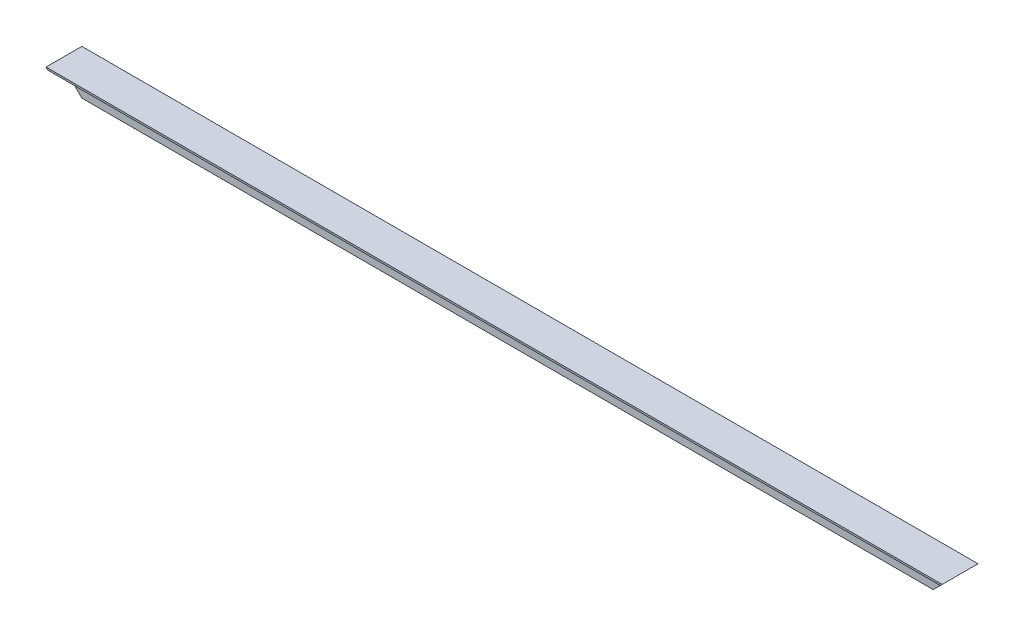
SolidWorks part; units mm, degrees
ref_plane "Front Plane" through (0, 0, 0) normal (0, 0, 1) x (1, 0, 0)
ref_plane "Top Plane" through (0, 0, 0) normal (0, 1, 0) x (1, 0, 0)
ref_plane "Right Plane" through (0, 0, 0) normal (1, 0, 0) x (0, 0, -1)
sketch "Sketch6" plane through (0, 0, 0) normal (0, 0, 1) x (1, 0, 0)
  line L1 (-60.8582, 99.7811) -> (939.1418, 99.7811)
  line L2 (-60.8582, 99.7811) -> (-60.8582, 59.7811)
  line L3 (-60.8582, 59.7811) -> (939.1418, 59.7811)
  line L4 (939.1418, 99.7811) -> (939.1418, 59.7811)
  dimension "D1" = 1000
  dimension "D2" = 40
extrude "Boss-Extrude3" add sketch "Sketch6" along normal blind 40
sketch "Sketch7" plane through (-60.8582, 0, 0) normal (-1, 0, 0) x (0, 0, 1)
  line L6 (0, 99.7811) -> (0, 59.7811) construction
  line L7 (2, 74.7811) -> (40, 74.7811)
  line L8 (2, 74.7811) -> (2, 59.7811)
  line L9 (2, 59.7811) -> (40, 59.7811)
  line L10 (40, 74.7811) -> (40, 59.7811)
  line L11 (25, 97.7811) -> (40, 97.7811)
  line L12 (25, 97.7811) -> (25, 74.7811)
  line L13 (25, 74.7811) -> (40, 74.7811)
  line L14 (40, 97.7811) -> (40, 74.7811)
  line L15 (40, 59.7811) -> (0, 59.7811) construction
  line L16 (40, 99.7811) -> (40, 59.7811) construction
  line L17 (40, 99.7811) -> (0, 99.7811) construction
  line M10 (0, 59.7811) -> (40, 59.7811)
  line M11 (40, 59.7811) -> (40, 99.7811)
  dimension "D1" = 2
  dimension "D2" = 0
  dimension "D3" = 0
  dimension "D4" = 25
  dimension "D5" = 2
  dimension "D6" = 0
  dimension "D7" = 25
  dimension "D8" = 0
extrude "Cut-Extrude3" cut sketch "Sketch7" against normal blind 1064 contours L11 L12 L7 M11 | L7 L8 M10 M11
sketch "Sketch8" plane through (0, 0, 0) normal (0, 0, -1) x (-1, 0, 0)
  line L5 (-939.1418, 99.7811) -> (-899.1418, 59.7811)
  line L6 (60.8582, 59.7811) -> (-939.1418, 59.7811) construction
  line L7 (-899.1418, 59.7811) -> (-939.1418, 59.7811)
  line L8 (-939.1418, 59.7811) -> (-939.1418, 99.7811)
  line L9 (60.8582, 59.7811) -> (20.8582, 59.7811)
  line L10 (20.8582, 59.7811) -> (60.8582, 99.7811)
  line L11 (60.8582, 99.7811) -> (60.8582, 59.7811)
  dimension "D1" = 40
  dimension "D2" = 40
  dimension "D3" = 40
extrude "Cut-Extrude4" cut sketch "Sketch8" against normal blind 1064
